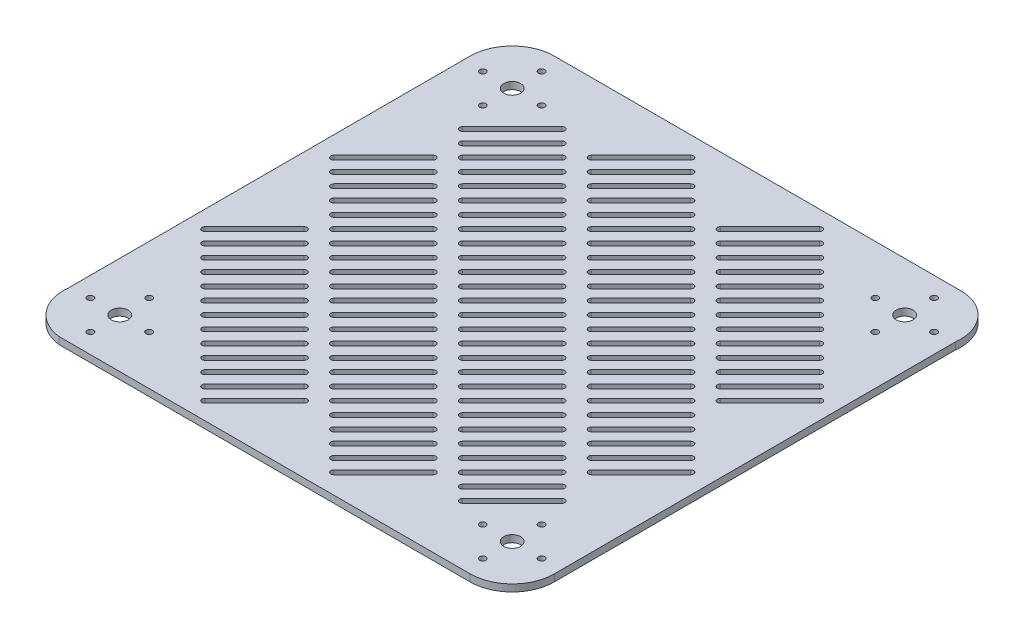
SolidWorks part; units mm, degrees
ref_plane "前视基准面" through (0, 0, 0) normal (0, 0, 1) x (1, 0, 0)
ref_plane "上视基准面" through (0, 0, 0) normal (0, 1, 0) x (1, 0, 0)
ref_plane "右视基准面" through (0, 0, 0) normal (1, 0, 0) x (0, 0, -1)
sketch "草图5" plane through (0, 0, 0) normal (0, 1, 0) x (1, 0, 0)
  line L0 (-17.6777, -17.6777) -> (17.6777, 17.6777) construction
  line L5 (-145, 175.0001) -> (144.9999, 175.0001)
  line L6 (-175.0001, 145) -> (-175.0001, -141.539)
  line L7 (-148.4608, -175.0001) -> (145, -175.0001)
  line L8 (174.7909, 141.4627) -> (175.0001, -144.9781)
  line L9 (-175.0001, 175.0001) -> (175.0001, -175.0001) construction
  line L10 (-175, -175) -> (175, 175) construction
  line L15 (-26.5165, -8.8388) -> (8.8388, 26.5165) construction
  line L18 (-28.0414, -7.3139) -> (7.3139, 28.0414)
  line L21 (-24.9916, -10.3638) -> (10.3638, 24.9916)
  line L24 (-35.3553, 0) -> (0, 35.3553) construction
  line L27 (-36.8803, 1.5249) -> (-1.5249, 36.8803)
  line L30 (-33.8304, -1.5249) -> (1.5249, 33.8304)
  line L33 (-44.1942, 8.8388) -> (-8.8388, 44.1942) construction
  line L36 (-45.7191, 10.3638) -> (-10.3638, 45.7191)
  line L39 (-42.6692, 7.3139) -> (-7.3139, 42.6692)
  line L42 (-53.033, 17.6777) -> (-17.6777, 53.033) construction
  line L45 (-54.5579, 19.2026) -> (-19.2026, 54.5579)
  line L48 (-51.5081, 16.1527) -> (-16.1527, 51.5081)
  line L51 (-61.8718, 26.5165) -> (-26.5165, 61.8718) construction
  line L54 (-63.3968, 28.0414) -> (-28.0414, 63.3968)
  line L57 (-60.3469, 24.9916) -> (-24.9916, 60.3469)
  line L60 (-70.7107, 35.3553) -> (-35.3553, 70.7107) construction
  line L63 (-72.2356, 36.8803) -> (-36.8803, 72.2356)
  line L66 (-69.1857, 33.8304) -> (-33.8304, 69.1857)
  line L69 (-79.5495, 44.1942) -> (-44.1942, 79.5495) construction
  line L72 (-81.0744, 45.7191) -> (-45.7191, 81.0744)
  line L75 (-78.0246, 42.6692) -> (-42.6692, 78.0246)
  line L78 (-88.3883, 53.033) -> (-53.033, 88.3883) construction
  line L81 (-19.2026, -16.1527) -> (16.1527, 19.2026)
  line L82 (-16.1527, -19.2026) -> (19.2026, 16.1527)
  line L83 (-89.9133, 54.5579) -> (-54.5579, 89.9133)
  line L84 (-86.8634, 51.5081) -> (-51.5081, 86.8634)
  line L85 (-97.2272, 61.8718) -> (-61.8718, 97.2272) construction
  line L86 (-98.7521, 63.3968) -> (-63.3968, 98.7521)
  line L87 (-95.7023, 60.3469) -> (-60.3469, 95.7023)
  line L88 (-106.066, 70.7107) -> (-70.7107, 106.066) construction
  line L89 (-107.5909, 72.2356) -> (-72.2356, 107.5909)
  line L90 (-104.5411, 69.1857) -> (-69.1857, 104.5411)
  line L91 (-114.9049, 79.5495) -> (-79.5495, 114.9049) construction
  line L92 (-116.4298, 81.0744) -> (-81.0744, 116.4298)
  line L93 (-113.3799, 78.0246) -> (-78.0246, 113.3799)
  line L94 (-123.7437, 88.3883) -> (-88.3883, 123.7437) construction
  line L95 (-125.2686, 89.9133) -> (-89.9133, 125.2686)
  line L96 (-122.2188, 86.8634) -> (-86.8634, 122.2188)
  line L97 (-132.5825, 97.2272) -> (-97.2272, 132.5825) construction
  line L98 (-134.1075, 98.7521) -> (-98.7521, 134.1075)
  line L99 (-131.0576, 95.7023) -> (-95.7023, 131.0576)
  line L100 (-8.8388, -26.5165) -> (26.5165, 8.8388) construction
  line L101 (-10.3638, -24.9916) -> (24.9916, 10.3638)
  line L102 (-7.3139, -28.0414) -> (28.0414, 7.3139)
  line L103 (0, -35.3553) -> (35.3553, 0) construction
  line L104 (-1.5249, -33.8304) -> (33.8304, 1.5249)
  line L105 (1.5249, -36.8803) -> (36.8803, -1.5249)
  line L106 (8.8388, -44.1942) -> (44.1942, -8.8388) construction
  line L107 (7.3139, -42.6692) -> (42.6692, -7.3139)
  line L108 (10.3638, -45.7191) -> (45.7191, -10.3638)
  line L109 (17.6777, -53.033) -> (53.033, -17.6777) construction
  line L110 (16.1527, -51.5081) -> (51.5081, -16.1527)
  line L111 (19.2026, -54.5579) -> (54.5579, -19.2026)
  line L112 (26.5165, -61.8718) -> (61.8718, -26.5165) construction
  line L113 (24.9916, -60.3469) -> (60.3469, -24.9916)
  line L114 (28.0414, -63.3968) -> (63.3968, -28.0414)
  line L115 (35.3553, -70.7107) -> (70.7107, -35.3553) construction
  line L116 (33.8304, -69.1857) -> (69.1857, -33.8304)
  line L117 (36.8803, -72.2356) -> (72.2356, -36.8803)
  line L118 (44.1942, -79.5495) -> (79.5495, -44.1942) construction
  line L119 (42.6692, -78.0246) -> (78.0246, -42.6692)
  line L120 (45.7191, -81.0744) -> (81.0744, -45.7191)
  line L121 (53.033, -88.3883) -> (88.3883, -53.033) construction
  line L122 (51.5081, -86.8634) -> (86.8634, -51.5081)
  line L123 (54.5579, -89.9133) -> (89.9133, -54.5579)
  line L124 (61.8718, -97.2272) -> (97.2272, -61.8718) construction
  line L125 (60.3469, -95.7023) -> (95.7023, -60.3469)
  line L126 (63.3968, -98.7521) -> (98.7521, -63.3968)
  line L127 (70.7107, -106.066) -> (106.066, -70.7107) construction
  line L128 (69.1857, -104.5411) -> (104.5411, -69.1857)
  line L129 (72.2356, -107.5909) -> (107.5909, -72.2356)
  line L130 (79.5495, -114.9049) -> (114.9049, -79.5495) construction
  line L131 (78.0246, -113.3799) -> (113.3799, -78.0246)
  line L132 (81.0744, -116.4298) -> (116.4298, -81.0744)
  line L133 (88.3883, -123.7437) -> (123.7437, -88.3883) construction
  line L134 (86.8634, -122.2188) -> (122.2188, -86.8634)
  line L135 (89.9133, -125.2686) -> (125.2686, -89.9133)
  line L136 (97.2272, -132.5825) -> (132.5825, -97.2272) construction
  line L137 (95.7023, -131.0576) -> (131.0576, -95.7023)
  line L138 (98.7521, -134.1075) -> (134.1075, -98.7521)
  line L139 (28.2843, 28.2843) -> (63.6396, 63.6396) construction
  line L140 (26.7593, 29.8092) -> (62.1147, 65.1645)
  line L141 (29.8092, 26.7593) -> (65.1645, 62.1147)
  line L142 (74.2462, 74.2462) -> (109.6016, 109.6016) construction
  line L143 (72.7213, 75.7711) -> (108.0766, 111.1265)
  line L144 (75.7711, 72.7213) -> (111.1265, 108.0766)
  line L145 (19.4454, 37.1231) -> (54.8008, 72.4784) construction
  line L146 (17.9205, 38.648) -> (53.2758, 74.0034)
  line L147 (20.9704, 35.5982) -> (56.3257, 70.9535)
  line L148 (10.6066, 45.9619) -> (45.9619, 81.3173) construction
  line L149 (9.0817, 47.4869) -> (44.437, 82.8422)
  line L150 (12.1315, 44.437) -> (47.4869, 79.7924)
  line L151 (1.7678, 54.8008) -> (37.1231, 90.1561) construction
  line L152 (0.2428, 56.3257) -> (35.5982, 91.681)
  line L153 (3.2927, 53.2758) -> (38.648, 88.6312)
  line L154 (-7.0711, 63.6396) -> (28.2843, 98.9949) construction
  line L155 (-8.596, 65.1645) -> (26.7593, 100.5199)
  line L156 (-5.5461, 62.1147) -> (29.8092, 97.47)
  line L157 (-15.9099, 72.4784) -> (19.4454, 107.8338) construction
  line L158 (-17.4348, 74.0034) -> (17.9205, 109.3587)
  line L159 (-14.385, 70.9535) -> (20.9704, 106.3089)
  line L160 (-24.7487, 81.3173) -> (10.6066, 116.6726) construction
  line L161 (-26.2737, 82.8422) -> (9.0817, 118.1975)
  line L162 (-23.2238, 79.7924) -> (12.1315, 115.1477)
  line L163 (-33.5876, 90.1561) -> (1.7678, 125.5115) construction
  line L164 (-35.1125, 91.681) -> (0.2428, 127.0364)
  line L165 (-32.0626, 88.6312) -> (3.2927, 123.9865)
  line L166 (-42.4264, 98.9949) -> (-7.0711, 134.3503) construction
  line L167 (-43.9513, 100.5199) -> (-8.596, 135.8752)
  line L168 (-40.9015, 97.47) -> (-5.5461, 132.8254)
  line L169 (-51.2652, 107.8338) -> (-15.9099, 143.1891) construction
  line L170 (-52.7902, 109.3587) -> (-17.4348, 144.7141)
  line L171 (-49.7403, 106.3089) -> (-14.385, 141.6642)
  line L172 (-60.1041, 116.6726) -> (-24.7487, 152.028) construction
  line L173 (-61.629, 118.1975) -> (-26.2737, 153.5529)
  line L174 (-58.5791, 115.1477) -> (-23.2238, 150.503)
  line L175 (-68.9429, 125.5115) -> (-33.5876, 160.8668) construction
  line L176 (-70.4678, 127.0364) -> (-35.1125, 162.3917)
  line L177 (-67.418, 123.9865) -> (-32.0626, 159.3419)
  line L178 (37.1231, 19.4454) -> (72.4784, 54.8008) construction
  line L179 (35.5982, 20.9704) -> (70.9535, 56.3257)
  line L180 (38.648, 17.9205) -> (74.0034, 53.2758)
  line L181 (45.9619, 10.6066) -> (81.3173, 45.9619) construction
  line L182 (44.437, 12.1315) -> (79.7924, 47.4869)
  line L183 (47.4869, 9.0817) -> (82.8422, 44.437)
  line L184 (54.8008, 1.7678) -> (90.1561, 37.1231) construction
  line L185 (53.2758, 3.2927) -> (88.6312, 38.648)
  line L186 (56.3257, 0.2428) -> (91.681, 35.5982)
  line L187 (63.6396, -7.0711) -> (98.9949, 28.2843) construction
  line L188 (62.1147, -5.5461) -> (97.47, 29.8092)
  line L189 (65.1645, -8.596) -> (100.5199, 26.7593)
  line L190 (72.4784, -15.9099) -> (107.8338, 19.4454) construction
  line L191 (70.9535, -14.385) -> (106.3089, 20.9704)
  line L192 (74.0034, -17.4348) -> (109.3587, 17.9205)
  line L193 (81.3173, -24.7487) -> (116.6726, 10.6066) construction
  line L194 (79.7924, -23.2238) -> (115.1477, 12.1315)
  line L195 (82.8422, -26.2737) -> (118.1975, 9.0817)
  line L196 (90.1561, -33.5876) -> (125.5115, 1.7678) construction
  line L197 (88.6312, -32.0626) -> (123.9865, 3.2927)
  line L198 (91.681, -35.1125) -> (127.0364, 0.2428)
  line L199 (98.9949, -42.4264) -> (134.3503, -7.0711) construction
  line L200 (97.47, -40.9015) -> (132.8254, -5.5461)
  line L201 (100.5199, -43.9513) -> (135.8752, -8.596)
  line L202 (107.8338, -51.2652) -> (143.1891, -15.9099) construction
  line L203 (106.3089, -49.7403) -> (141.6642, -14.385)
  line L204 (109.3587, -52.7902) -> (144.7141, -17.4348)
  line L205 (116.6726, -60.1041) -> (152.028, -24.7487) construction
  line L206 (115.1477, -58.5791) -> (150.503, -23.2238)
  line L207 (118.1975, -61.629) -> (153.5529, -26.2737)
  line L208 (125.5115, -68.9429) -> (160.8668, -33.5876) construction
  line L209 (123.9865, -67.418) -> (159.3419, -32.0626)
  line L210 (127.0364, -70.4678) -> (162.3917, -35.1125)
  line L211 (65.4074, 83.085) -> (100.7627, 118.4404) construction
  line L212 (63.8824, 84.61) -> (99.2378, 119.9653)
  line L213 (66.9323, 81.5601) -> (102.2876, 116.9155)
  line L214 (56.5685, 91.9239) -> (91.9239, 127.2792) construction
  line L215 (55.0436, 93.4488) -> (90.399, 128.8041)
  line L216 (58.0935, 90.399) -> (93.4488, 125.7543)
  line L217 (47.7297, 100.7627) -> (83.085, 136.1181) construction
  line L218 (46.2048, 102.2876) -> (81.5601, 137.643)
  line L219 (49.2546, 99.2378) -> (84.61, 134.5931)
  line L220 (38.8909, 109.6016) -> (74.2462, 144.9569) construction
  line L221 (37.3659, 111.1265) -> (72.7213, 146.4818)
  line L222 (40.4158, 108.0766) -> (75.7711, 143.432)
  line L223 (30.052, 118.4404) -> (65.4074, 153.7957) construction
  line L224 (28.5271, 119.9653) -> (63.8824, 155.3207)
  line L225 (31.577, 116.9155) -> (66.9323, 152.2708)
  line L226 (21.2132, 127.2792) -> (56.5685, 162.6346) construction
  line L227 (19.6883, 128.8041) -> (55.0436, 164.1595)
  line L228 (22.7381, 125.7543) -> (58.0935, 161.1096)
  line L229 (83.085, 65.4074) -> (118.4404, 100.7627) construction
  line L230 (81.5601, 66.9323) -> (116.9155, 102.2876)
  line L231 (84.61, 63.8824) -> (119.9653, 99.2378)
  line L232 (91.9239, 56.5685) -> (127.2792, 91.9239) construction
  line L233 (90.399, 58.0935) -> (125.7543, 93.4488)
  line L234 (93.4488, 55.0436) -> (128.8041, 90.399)
  line L235 (100.7627, 47.7297) -> (136.1181, 83.085) construction
  line L236 (99.2378, 49.2546) -> (134.5931, 84.61)
  line L237 (102.2876, 46.2048) -> (137.643, 81.5601)
  line L238 (109.6016, 38.8909) -> (144.9569, 74.2462) construction
  line L239 (108.0766, 40.4158) -> (143.432, 75.7711)
  line L240 (111.1265, 37.3659) -> (146.4818, 72.7213)
  line L241 (118.4404, 30.052) -> (153.7957, 65.4074) construction
  line L242 (116.9155, 31.577) -> (152.2708, 66.9323)
  line L243 (119.9653, 28.5271) -> (155.3207, 63.8824)
  line L244 (127.2792, 21.2132) -> (162.6346, 56.5685) construction
  line L245 (125.7543, 22.7381) -> (161.1096, 58.0935)
  line L246 (128.8041, 19.6883) -> (164.1595, 55.0436)
  line L247 (-63.6396, -63.6396) -> (-28.2843, -28.2843) construction
  line L248 (-65.1645, -62.1147) -> (-29.8092, -26.7593)
  line L249 (-62.1147, -65.1645) -> (-26.7593, -29.8092)
  line L250 (-109.6016, -109.6016) -> (-74.2462, -74.2462) construction
  line L251 (-111.1265, -108.0766) -> (-75.7711, -72.7213)
  line L252 (-108.0766, -111.1265) -> (-72.7213, -75.7711)
  line L253 (-72.4784, -54.8008) -> (-37.1231, -19.4454) construction
  line L254 (-74.0034, -53.2758) -> (-38.648, -17.9205)
  line L255 (-70.9535, -56.3257) -> (-35.5982, -20.9704)
  line L256 (-81.3173, -45.9619) -> (-45.9619, -10.6066) construction
  line L257 (-82.8422, -44.437) -> (-47.4869, -9.0817)
  line L258 (-79.7924, -47.4869) -> (-44.437, -12.1315)
  line L259 (-90.1561, -37.1231) -> (-54.8008, -1.7678) construction
  line L260 (-91.681, -35.5982) -> (-56.3257, -0.2428)
  line L261 (-88.6312, -38.648) -> (-53.2758, -3.2927)
  line L262 (-98.9949, -28.2843) -> (-63.6396, 7.0711) construction
  line L263 (-100.5199, -26.7593) -> (-65.1645, 8.596)
  line L264 (-97.47, -29.8092) -> (-62.1147, 5.5461)
  line L265 (-107.8338, -19.4454) -> (-72.4784, 15.9099) construction
  line L266 (-109.3587, -17.9205) -> (-74.0034, 17.4348)
  line L267 (-106.3089, -20.9704) -> (-70.9535, 14.385)
  line L268 (-116.6726, -10.6066) -> (-81.3173, 24.7487) construction
  line L269 (-118.1975, -9.0817) -> (-82.8422, 26.2737)
  line L270 (-115.1477, -12.1315) -> (-79.7924, 23.2238)
  line L271 (-125.5115, -1.7678) -> (-90.1561, 33.5876) construction
  line L272 (-127.0364, -0.2428) -> (-91.681, 35.1125)
  line L273 (-123.9865, -3.2927) -> (-88.6312, 32.0626)
  line L274 (-134.3503, 7.0711) -> (-98.9949, 42.4264) construction
  line L275 (-135.8752, 8.596) -> (-100.5199, 43.9513)
  line L276 (-132.8254, 5.5461) -> (-97.47, 40.9015)
  line L277 (-143.1891, 15.9099) -> (-107.8338, 51.2652) construction
  line L278 (-144.7141, 17.4348) -> (-109.3587, 52.7902)
  line L279 (-141.6642, 14.385) -> (-106.3089, 49.7403)
  line L280 (-152.028, 24.7487) -> (-116.6726, 60.1041) construction
  line L281 (-153.5529, 26.2737) -> (-118.1975, 61.629)
  line L282 (-150.503, 23.2238) -> (-115.1477, 58.5791)
  line L283 (-160.8668, 33.5876) -> (-125.5115, 68.9429) construction
  line L284 (-162.3917, 35.1125) -> (-127.0364, 70.4678)
  line L285 (-159.3419, 32.0626) -> (-123.9865, 67.418)
  line L286 (-54.8008, -72.4784) -> (-19.4454, -37.1231) construction
  line L287 (-56.3257, -70.9535) -> (-20.9704, -35.5982)
  line L288 (-53.2758, -74.0034) -> (-17.9205, -38.648)
  line L289 (-45.9619, -81.3173) -> (-10.6066, -45.9619) construction
  line L290 (-47.4869, -79.7924) -> (-12.1315, -44.437)
  line L291 (-44.437, -82.8422) -> (-9.0817, -47.4869)
  line L292 (-37.1231, -90.1561) -> (-1.7678, -54.8008) construction
  line L293 (-38.648, -88.6312) -> (-3.2927, -53.2758)
  line L294 (-35.5982, -91.681) -> (-0.2428, -56.3257)
  line L295 (-28.2843, -98.9949) -> (7.0711, -63.6396) construction
  line L296 (-29.8092, -97.47) -> (5.5461, -62.1147)
  line L297 (-26.7593, -100.5199) -> (8.596, -65.1645)
  line L298 (-19.4454, -107.8338) -> (15.9099, -72.4784) construction
  line L299 (-20.9704, -106.3089) -> (14.385, -70.9535)
  line L300 (-17.9205, -109.3587) -> (17.4348, -74.0034)
  line L301 (-10.6066, -116.6726) -> (24.7487, -81.3173) construction
  line L302 (-12.1315, -115.1477) -> (23.2238, -79.7924)
  line L303 (-9.0817, -118.1975) -> (26.2737, -82.8422)
  line L304 (-1.7678, -125.5115) -> (33.5876, -90.1561) construction
  line L305 (-3.2927, -123.9865) -> (32.0626, -88.6312)
  line L306 (-0.2428, -127.0364) -> (35.1125, -91.681)
  line L307 (7.0711, -134.3503) -> (42.4264, -98.9949) construction
  line L308 (5.5461, -132.8254) -> (40.9015, -97.47)
  line L309 (8.596, -135.8752) -> (43.9513, -100.5199)
  line L310 (15.9099, -143.1891) -> (51.2652, -107.8338) construction
  line L311 (14.385, -141.6642) -> (49.7403, -106.3089)
  line L312 (17.4348, -144.7141) -> (52.7902, -109.3587)
  line L313 (24.7487, -152.028) -> (60.1041, -116.6726) construction
  line L314 (23.2238, -150.503) -> (58.5791, -115.1477)
  line L315 (26.2737, -153.5529) -> (61.629, -118.1975)
  line L316 (33.5876, -160.8668) -> (68.9429, -125.5115) construction
  line L317 (32.0626, -159.3419) -> (67.418, -123.9865)
  line L318 (35.1125, -162.3917) -> (70.4678, -127.0364)
  line L319 (-100.7627, -118.4404) -> (-65.4074, -83.085) construction
  line L320 (-102.2876, -116.9155) -> (-66.9323, -81.5601)
  line L321 (-99.2378, -119.9653) -> (-63.8824, -84.61)
  line L322 (-91.9239, -127.2792) -> (-56.5685, -91.9239) construction
  line L323 (-93.4488, -125.7543) -> (-58.0935, -90.399)
  line L324 (-90.399, -128.8041) -> (-55.0436, -93.4488)
  line L325 (-83.085, -136.1181) -> (-47.7297, -100.7627) construction
  line L326 (-84.61, -134.5931) -> (-49.2546, -99.2378)
  line L327 (-81.5601, -137.643) -> (-46.2048, -102.2876)
  line L328 (-74.2462, -144.9569) -> (-38.8909, -109.6016) construction
  line L329 (-75.7711, -143.432) -> (-40.4158, -108.0766)
  line L330 (-72.7213, -146.4818) -> (-37.3659, -111.1265)
  line L331 (-65.4074, -153.7957) -> (-30.052, -118.4404) construction
  line L332 (-66.9323, -152.2708) -> (-31.577, -116.9155)
  line L333 (-63.8824, -155.3207) -> (-28.5271, -119.9653)
  line L334 (-56.5685, -162.6346) -> (-21.2132, -127.2792) construction
  line L335 (-58.0935, -161.1096) -> (-22.7381, -125.7543)
  line L336 (-55.0436, -164.1595) -> (-19.6883, -128.8041)
  line L337 (-118.4404, -100.7627) -> (-83.085, -65.4074) construction
  line L338 (-119.9653, -99.2378) -> (-84.61, -63.8824)
  line L339 (-116.9155, -102.2876) -> (-81.5601, -66.9323)
  line L340 (-127.2792, -91.9239) -> (-91.9239, -56.5685) construction
  line L341 (-128.8041, -90.399) -> (-93.4488, -55.0436)
  line L342 (-125.7543, -93.4488) -> (-90.399, -58.0935)
  line L343 (-136.1181, -83.085) -> (-100.7627, -47.7297) construction
  line L344 (-137.643, -81.5601) -> (-102.2876, -46.2048)
  line L345 (-134.5931, -84.61) -> (-99.2378, -49.2546)
  line L346 (-144.9569, -74.2462) -> (-109.6016, -38.8909) construction
  line L347 (-146.4818, -72.7213) -> (-111.1265, -37.3659)
  line L348 (-143.432, -75.7711) -> (-108.0766, -40.4158)
  line L349 (-153.7957, -65.4074) -> (-118.4404, -30.052) construction
  line L350 (-155.3207, -63.8824) -> (-119.9653, -28.5271)
  line L351 (-152.2708, -66.9323) -> (-116.9155, -31.577)
  line L352 (-162.6346, -56.5685) -> (-127.2792, -21.2132) construction
  line L353 (-164.1595, -55.0436) -> (-128.8041, -19.6883)
  line L354 (-161.1096, -58.0935) -> (-125.7543, -22.7381)
  arc A0 (174.7909, 141.4627) -> (144.9999, 175.0001) centre (144.9999, 144.9999) ccw
  arc A1 (175.0001, -144.9781) -> (145, -175.0001) centre (145, -145) cw
  arc A2 (-148.4608, -175.0001) -> (-175.0001, -141.539) centre (-144.9999, -144.9999) cw
  arc A3 (-175.0001, 145) -> (-145, 175.0001) centre (-145, 145) cw
  circle A5 centre (140, 119) radius 2.25
  circle A6 centre (161, 140) radius 2.25
  circle A7 centre (140, 161) radius 2.25
  circle A8 centre (119, 140) radius 2.25
  circle A9 centre (140, 140) radius 6.02
  circle A11 centre (140, -161) radius 2.25
  circle A12 centre (161, -140) radius 2.25
  circle A13 centre (140, -119) radius 2.25
  circle A14 centre (119, -140) radius 2.25
  circle A15 centre (140, -140) radius 6.02
  circle A17 centre (-140, 119) radius 2.25
  circle A18 centre (-119, 140) radius 2.25
  circle A19 centre (-140, 161) radius 2.25
  circle A20 centre (-161, 140) radius 2.25
  circle A21 centre (-140, 140) radius 6.02
  circle A23 centre (-140, -161) radius 2.25
  circle A24 centre (-119, -140.0405) radius 2.25
  circle A25 centre (-140, -119) radius 2.25
  circle A26 centre (-161, -140) radius 2.25
  circle A27 centre (-140, -140.0405) radius 6.02
  arc A76 (-19.2026, -16.1527) -> (-16.1527, -19.2026) centre (-17.6777, -17.6777) ccw
  arc A77 (19.2026, 16.1527) -> (16.1527, 19.2026) centre (17.6777, 17.6777) ccw
  arc A78 (-28.0414, -7.3139) -> (-24.9916, -10.3638) centre (-26.5165, -8.8388) ccw
  arc A79 (10.3638, 24.9916) -> (7.3139, 28.0414) centre (8.8388, 26.5165) ccw
  arc A80 (-36.8803, 1.5249) -> (-33.8304, -1.5249) centre (-35.3553, 0) ccw
  arc A81 (1.5249, 33.8304) -> (-1.5249, 36.8803) centre (0, 35.3553) ccw
  arc A82 (-45.7191, 10.3638) -> (-42.6692, 7.3139) centre (-44.1942, 8.8388) ccw
  arc A83 (-7.3139, 42.6692) -> (-10.3638, 45.7191) centre (-8.8388, 44.1942) ccw
  arc A84 (-54.5579, 19.2026) -> (-51.5081, 16.1527) centre (-53.033, 17.6777) ccw
  arc A85 (-16.1527, 51.5081) -> (-19.2026, 54.5579) centre (-17.6777, 53.033) ccw
  arc A86 (-63.3968, 28.0414) -> (-60.3469, 24.9916) centre (-61.8718, 26.5165) ccw
  arc A87 (-24.9916, 60.3469) -> (-28.0414, 63.3968) centre (-26.5165, 61.8718) ccw
  arc A88 (-72.2356, 36.8803) -> (-69.1857, 33.8304) centre (-70.7107, 35.3553) ccw
  arc A89 (-33.8304, 69.1857) -> (-36.8803, 72.2356) centre (-35.3553, 70.7107) ccw
  arc A90 (-81.0744, 45.7191) -> (-78.0246, 42.6692) centre (-79.5495, 44.1942) ccw
  arc A91 (-42.6692, 78.0246) -> (-45.7191, 81.0744) centre (-44.1942, 79.5495) ccw
  arc A92 (-89.9133, 54.5579) -> (-86.8634, 51.5081) centre (-88.3883, 53.033) ccw
  arc A93 (-51.5081, 86.8634) -> (-54.5579, 89.9133) centre (-53.033, 88.3883) ccw
  arc A94 (-98.7521, 63.3968) -> (-95.7023, 60.3469) centre (-97.2272, 61.8718) ccw
  arc A95 (-60.3469, 95.7023) -> (-63.3968, 98.7521) centre (-61.8718, 97.2272) ccw
  arc A96 (-107.5909, 72.2356) -> (-104.5411, 69.1857) centre (-106.066, 70.7107) ccw
  arc A97 (-69.1857, 104.5411) -> (-72.2356, 107.5909) centre (-70.7107, 106.066) ccw
  arc A98 (-116.4298, 81.0744) -> (-113.3799, 78.0246) centre (-114.9049, 79.5495) ccw
  arc A99 (-78.0246, 113.3799) -> (-81.0744, 116.4298) centre (-79.5495, 114.9049) ccw
  arc A100 (-125.2686, 89.9133) -> (-122.2188, 86.8634) centre (-123.7437, 88.3883) ccw
  arc A101 (-86.8634, 122.2188) -> (-89.9133, 125.2686) centre (-88.3883, 123.7437) ccw
  arc A102 (-134.1075, 98.7521) -> (-131.0576, 95.7023) centre (-132.5825, 97.2272) ccw
  arc A103 (-95.7023, 131.0576) -> (-98.7521, 134.1075) centre (-97.2272, 132.5825) ccw
  arc A104 (-10.3638, -24.9916) -> (-7.3139, -28.0414) centre (-8.8388, -26.5165) ccw
  arc A105 (28.0414, 7.3139) -> (24.9916, 10.3638) centre (26.5165, 8.8388) ccw
  arc A106 (-1.5249, -33.8304) -> (1.5249, -36.8803) centre (0, -35.3553) ccw
  arc A107 (36.8803, -1.5249) -> (33.8304, 1.5249) centre (35.3553, 0) ccw
  arc A108 (7.3139, -42.6692) -> (10.3638, -45.7191) centre (8.8388, -44.1942) ccw
  arc A109 (45.7191, -10.3638) -> (42.6692, -7.3139) centre (44.1942, -8.8388) ccw
  arc A110 (16.1527, -51.5081) -> (19.2026, -54.5579) centre (17.6777, -53.033) ccw
  arc A111 (54.5579, -19.2026) -> (51.5081, -16.1527) centre (53.033, -17.6777) ccw
  arc A112 (24.9916, -60.3469) -> (28.0414, -63.3968) centre (26.5165, -61.8718) ccw
  arc A113 (63.3968, -28.0414) -> (60.3469, -24.9916) centre (61.8718, -26.5165) ccw
  arc A114 (33.8304, -69.1857) -> (36.8803, -72.2356) centre (35.3553, -70.7107) ccw
  arc A115 (72.2356, -36.8803) -> (69.1857, -33.8304) centre (70.7107, -35.3553) ccw
  arc A116 (42.6692, -78.0246) -> (45.7191, -81.0744) centre (44.1942, -79.5495) ccw
  arc A117 (81.0744, -45.7191) -> (78.0246, -42.6692) centre (79.5495, -44.1942) ccw
  arc A118 (51.5081, -86.8634) -> (54.5579, -89.9133) centre (53.033, -88.3883) ccw
  arc A119 (89.9133, -54.5579) -> (86.8634, -51.5081) centre (88.3883, -53.033) ccw
  arc A120 (60.3469, -95.7023) -> (63.3968, -98.7521) centre (61.8718, -97.2272) ccw
  arc A121 (98.7521, -63.3968) -> (95.7023, -60.3469) centre (97.2272, -61.8718) ccw
  arc A122 (69.1857, -104.5411) -> (72.2356, -107.5909) centre (70.7107, -106.066) ccw
  arc A123 (107.5909, -72.2356) -> (104.5411, -69.1857) centre (106.066, -70.7107) ccw
  arc A124 (78.0246, -113.3799) -> (81.0744, -116.4298) centre (79.5495, -114.9049) ccw
  arc A125 (116.4298, -81.0744) -> (113.3799, -78.0246) centre (114.9049, -79.5495) ccw
  arc A126 (86.8634, -122.2188) -> (89.9133, -125.2686) centre (88.3883, -123.7437) ccw
  arc A127 (125.2686, -89.9133) -> (122.2188, -86.8634) centre (123.7437, -88.3883) ccw
  arc A128 (95.7023, -131.0576) -> (98.7521, -134.1075) centre (97.2272, -132.5825) ccw
  arc A129 (134.1075, -98.7521) -> (131.0576, -95.7023) centre (132.5825, -97.2272) ccw
  arc A130 (26.7593, 29.8092) -> (29.8092, 26.7593) centre (28.2843, 28.2843) ccw
  arc A131 (65.1645, 62.1147) -> (62.1147, 65.1645) centre (63.6396, 63.6396) ccw
  arc A132 (72.7213, 75.7711) -> (75.7711, 72.7213) centre (74.2462, 74.2462) ccw
  arc A133 (111.1265, 108.0766) -> (108.0766, 111.1265) centre (109.6016, 109.6016) ccw
  arc A134 (17.9205, 38.648) -> (20.9704, 35.5982) centre (19.4454, 37.1231) ccw
  arc A135 (56.3257, 70.9535) -> (53.2758, 74.0034) centre (54.8008, 72.4784) ccw
  arc A136 (9.0817, 47.4869) -> (12.1315, 44.437) centre (10.6066, 45.9619) ccw
  arc A137 (47.4869, 79.7924) -> (44.437, 82.8422) centre (45.9619, 81.3173) ccw
  arc A138 (0.2428, 56.3257) -> (3.2927, 53.2758) centre (1.7678, 54.8008) ccw
  arc A139 (38.648, 88.6312) -> (35.5982, 91.681) centre (37.1231, 90.1561) ccw
  arc A140 (-8.596, 65.1645) -> (-5.5461, 62.1147) centre (-7.0711, 63.6396) ccw
  arc A141 (29.8092, 97.47) -> (26.7593, 100.5199) centre (28.2843, 98.9949) ccw
  arc A142 (-17.4348, 74.0034) -> (-14.385, 70.9535) centre (-15.9099, 72.4784) ccw
  arc A143 (20.9704, 106.3089) -> (17.9205, 109.3587) centre (19.4454, 107.8338) ccw
  arc A144 (-26.2737, 82.8422) -> (-23.2238, 79.7924) centre (-24.7487, 81.3173) ccw
  arc A145 (12.1315, 115.1477) -> (9.0817, 118.1975) centre (10.6066, 116.6726) ccw
  arc A146 (-35.1125, 91.681) -> (-32.0626, 88.6312) centre (-33.5876, 90.1561) ccw
  arc A147 (3.2927, 123.9865) -> (0.2428, 127.0364) centre (1.7678, 125.5115) ccw
  arc A148 (-43.9513, 100.5199) -> (-40.9015, 97.47) centre (-42.4264, 98.9949) ccw
  arc A149 (-5.5461, 132.8254) -> (-8.596, 135.8752) centre (-7.0711, 134.3503) ccw
  arc A150 (-52.7902, 109.3587) -> (-49.7403, 106.3089) centre (-51.2652, 107.8338) ccw
  arc A151 (-14.385, 141.6642) -> (-17.4348, 144.7141) centre (-15.9099, 143.1891) ccw
  arc A152 (-61.629, 118.1975) -> (-58.5791, 115.1477) centre (-60.1041, 116.6726) ccw
  arc A153 (-23.2238, 150.503) -> (-26.2737, 153.5529) centre (-24.7487, 152.028) ccw
  arc A154 (-70.4678, 127.0364) -> (-67.418, 123.9865) centre (-68.9429, 125.5115) ccw
  arc A155 (-32.0626, 159.3419) -> (-35.1125, 162.3917) centre (-33.5876, 160.8668) ccw
  arc A156 (35.5982, 20.9704) -> (38.648, 17.9205) centre (37.1231, 19.4454) ccw
  arc A157 (74.0034, 53.2758) -> (70.9535, 56.3257) centre (72.4784, 54.8008) ccw
  arc A158 (44.437, 12.1315) -> (47.4869, 9.0817) centre (45.9619, 10.6066) ccw
  arc A159 (82.8422, 44.437) -> (79.7924, 47.4869) centre (81.3173, 45.9619) ccw
  arc A160 (53.2758, 3.2927) -> (56.3257, 0.2428) centre (54.8008, 1.7678) ccw
  arc A161 (91.681, 35.5982) -> (88.6312, 38.648) centre (90.1561, 37.1231) ccw
  arc A162 (62.1147, -5.5461) -> (65.1645, -8.596) centre (63.6396, -7.0711) ccw
  arc A163 (100.5199, 26.7593) -> (97.47, 29.8092) centre (98.9949, 28.2843) ccw
  arc A164 (70.9535, -14.385) -> (74.0034, -17.4348) centre (72.4784, -15.9099) ccw
  arc A165 (109.3587, 17.9205) -> (106.3089, 20.9704) centre (107.8338, 19.4454) ccw
  arc A166 (79.7924, -23.2238) -> (82.8422, -26.2737) centre (81.3173, -24.7487) ccw
  arc A167 (118.1975, 9.0817) -> (115.1477, 12.1315) centre (116.6726, 10.6066) ccw
  arc A168 (88.6312, -32.0626) -> (91.681, -35.1125) centre (90.1561, -33.5876) ccw
  arc A169 (127.0364, 0.2428) -> (123.9865, 3.2927) centre (125.5115, 1.7678) ccw
  arc A170 (97.47, -40.9015) -> (100.5199, -43.9513) centre (98.9949, -42.4264) ccw
  arc A171 (135.8752, -8.596) -> (132.8254, -5.5461) centre (134.3503, -7.0711) ccw
  arc A172 (106.3089, -49.7403) -> (109.3587, -52.7902) centre (107.8338, -51.2652) ccw
  arc A173 (144.7141, -17.4348) -> (141.6642, -14.385) centre (143.1891, -15.9099) ccw
  arc A174 (115.1477, -58.5791) -> (118.1975, -61.629) centre (116.6726, -60.1041) ccw
  arc A175 (153.5529, -26.2737) -> (150.503, -23.2238) centre (152.028, -24.7487) ccw
  arc A176 (123.9865, -67.418) -> (127.0364, -70.4678) centre (125.5115, -68.9429) ccw
  arc A177 (162.3917, -35.1125) -> (159.3419, -32.0626) centre (160.8668, -33.5876) ccw
  arc A178 (63.8824, 84.61) -> (66.9323, 81.5601) centre (65.4074, 83.085) ccw
  arc A179 (102.2876, 116.9155) -> (99.2378, 119.9653) centre (100.7627, 118.4404) ccw
  arc A180 (55.0436, 93.4488) -> (58.0935, 90.399) centre (56.5685, 91.9239) ccw
  arc A181 (93.4488, 125.7543) -> (90.399, 128.8041) centre (91.9239, 127.2792) ccw
  arc A182 (46.2048, 102.2876) -> (49.2546, 99.2378) centre (47.7297, 100.7627) ccw
  arc A183 (84.61, 134.5931) -> (81.5601, 137.643) centre (83.085, 136.1181) ccw
  arc A184 (37.3659, 111.1265) -> (40.4158, 108.0766) centre (38.8909, 109.6016) ccw
  arc A185 (75.7711, 143.432) -> (72.7213, 146.4818) centre (74.2462, 144.9569) ccw
  arc A186 (28.5271, 119.9653) -> (31.577, 116.9155) centre (30.052, 118.4404) ccw
  arc A187 (66.9323, 152.2708) -> (63.8824, 155.3207) centre (65.4074, 153.7957) ccw
  arc A188 (19.6883, 128.8041) -> (22.7381, 125.7543) centre (21.2132, 127.2792) ccw
  arc A189 (58.0935, 161.1096) -> (55.0436, 164.1595) centre (56.5685, 162.6346) ccw
  arc A190 (81.5601, 66.9323) -> (84.61, 63.8824) centre (83.085, 65.4074) ccw
  arc A191 (119.9653, 99.2378) -> (116.9155, 102.2876) centre (118.4404, 100.7627) ccw
  arc A192 (90.399, 58.0935) -> (93.4488, 55.0436) centre (91.9239, 56.5685) ccw
  arc A193 (128.8041, 90.399) -> (125.7543, 93.4488) centre (127.2792, 91.9239) ccw
  arc A194 (99.2378, 49.2546) -> (102.2876, 46.2048) centre (100.7627, 47.7297) ccw
  arc A195 (137.643, 81.5601) -> (134.5931, 84.61) centre (136.1181, 83.085) ccw
  arc A196 (108.0766, 40.4158) -> (111.1265, 37.3659) centre (109.6016, 38.8909) ccw
  arc A197 (146.4818, 72.7213) -> (143.432, 75.7711) centre (144.9569, 74.2462) ccw
  arc A198 (116.9155, 31.577) -> (119.9653, 28.5271) centre (118.4404, 30.052) ccw
  arc A199 (155.3207, 63.8824) -> (152.2708, 66.9323) centre (153.7957, 65.4074) ccw
  arc A200 (125.7543, 22.7381) -> (128.8041, 19.6883) centre (127.2792, 21.2132) ccw
  arc A201 (164.1595, 55.0436) -> (161.1096, 58.0935) centre (162.6346, 56.5685) ccw
  arc A202 (-65.1645, -62.1147) -> (-62.1147, -65.1645) centre (-63.6396, -63.6396) ccw
  arc A203 (-26.7593, -29.8092) -> (-29.8092, -26.7593) centre (-28.2843, -28.2843) ccw
  arc A204 (-111.1265, -108.0766) -> (-108.0766, -111.1265) centre (-109.6016, -109.6016) ccw
  arc A205 (-72.7213, -75.7711) -> (-75.7711, -72.7213) centre (-74.2462, -74.2462) ccw
  arc A206 (-74.0034, -53.2758) -> (-70.9535, -56.3257) centre (-72.4784, -54.8008) ccw
  arc A207 (-35.5982, -20.9704) -> (-38.648, -17.9205) centre (-37.1231, -19.4454) ccw
  arc A208 (-82.8422, -44.437) -> (-79.7924, -47.4869) centre (-81.3173, -45.9619) ccw
  arc A209 (-44.437, -12.1315) -> (-47.4869, -9.0817) centre (-45.9619, -10.6066) ccw
  arc A210 (-91.681, -35.5982) -> (-88.6312, -38.648) centre (-90.1561, -37.1231) ccw
  arc A211 (-53.2758, -3.2927) -> (-56.3257, -0.2428) centre (-54.8008, -1.7678) ccw
  arc A212 (-100.5199, -26.7593) -> (-97.47, -29.8092) centre (-98.9949, -28.2843) ccw
  arc A213 (-62.1147, 5.5461) -> (-65.1645, 8.596) centre (-63.6396, 7.0711) ccw
  arc A214 (-109.3587, -17.9205) -> (-106.3089, -20.9704) centre (-107.8338, -19.4454) ccw
  arc A215 (-70.9535, 14.385) -> (-74.0034, 17.4348) centre (-72.4784, 15.9099) ccw
  arc A216 (-118.1975, -9.0817) -> (-115.1477, -12.1315) centre (-116.6726, -10.6066) ccw
  arc A217 (-79.7924, 23.2238) -> (-82.8422, 26.2737) centre (-81.3173, 24.7487) ccw
  arc A218 (-127.0364, -0.2428) -> (-123.9865, -3.2927) centre (-125.5115, -1.7678) ccw
  arc A219 (-88.6312, 32.0626) -> (-91.681, 35.1125) centre (-90.1561, 33.5876) ccw
  arc A220 (-135.8752, 8.596) -> (-132.8254, 5.5461) centre (-134.3503, 7.0711) ccw
  arc A221 (-97.47, 40.9015) -> (-100.5199, 43.9513) centre (-98.9949, 42.4264) ccw
  arc A222 (-144.7141, 17.4348) -> (-141.6642, 14.385) centre (-143.1891, 15.9099) ccw
  arc A223 (-106.3089, 49.7403) -> (-109.3587, 52.7902) centre (-107.8338, 51.2652) ccw
  arc A224 (-153.5529, 26.2737) -> (-150.503, 23.2238) centre (-152.028, 24.7487) ccw
  arc A225 (-115.1477, 58.5791) -> (-118.1975, 61.629) centre (-116.6726, 60.1041) ccw
  arc A226 (-162.3917, 35.1125) -> (-159.3419, 32.0626) centre (-160.8668, 33.5876) ccw
  arc A227 (-123.9865, 67.418) -> (-127.0364, 70.4678) centre (-125.5115, 68.9429) ccw
  arc A228 (-56.3257, -70.9535) -> (-53.2758, -74.0034) centre (-54.8008, -72.4784) ccw
  arc A229 (-17.9205, -38.648) -> (-20.9704, -35.5982) centre (-19.4454, -37.1231) ccw
  arc A230 (-47.4869, -79.7924) -> (-44.437, -82.8422) centre (-45.9619, -81.3173) ccw
  arc A231 (-9.0817, -47.4869) -> (-12.1315, -44.437) centre (-10.6066, -45.9619) ccw
  arc A232 (-38.648, -88.6312) -> (-35.5982, -91.681) centre (-37.1231, -90.1561) ccw
  arc A233 (-0.2428, -56.3257) -> (-3.2927, -53.2758) centre (-1.7678, -54.8008) ccw
  arc A234 (-29.8092, -97.47) -> (-26.7593, -100.5199) centre (-28.2843, -98.9949) ccw
  arc A235 (8.596, -65.1645) -> (5.5461, -62.1147) centre (7.0711, -63.6396) ccw
  arc A236 (-20.9704, -106.3089) -> (-17.9205, -109.3587) centre (-19.4454, -107.8338) ccw
  arc A237 (17.4348, -74.0034) -> (14.385, -70.9535) centre (15.9099, -72.4784) ccw
  arc A238 (-12.1315, -115.1477) -> (-9.0817, -118.1975) centre (-10.6066, -116.6726) ccw
  arc A239 (26.2737, -82.8422) -> (23.2238, -79.7924) centre (24.7487, -81.3173) ccw
  arc A240 (-3.2927, -123.9865) -> (-0.2428, -127.0364) centre (-1.7678, -125.5115) ccw
  arc A241 (35.1125, -91.681) -> (32.0626, -88.6312) centre (33.5876, -90.1561) ccw
  arc A242 (5.5461, -132.8254) -> (8.596, -135.8752) centre (7.0711, -134.3503) ccw
  arc A243 (43.9513, -100.5199) -> (40.9015, -97.47) centre (42.4264, -98.9949) ccw
  arc A244 (14.385, -141.6642) -> (17.4348, -144.7141) centre (15.9099, -143.1891) ccw
  arc A245 (52.7902, -109.3587) -> (49.7403, -106.3089) centre (51.2652, -107.8338) ccw
  arc A246 (23.2238, -150.503) -> (26.2737, -153.5529) centre (24.7487, -152.028) ccw
  arc A247 (61.629, -118.1975) -> (58.5791, -115.1477) centre (60.1041, -116.6726) ccw
  arc A248 (32.0626, -159.3419) -> (35.1125, -162.3917) centre (33.5876, -160.8668) ccw
  arc A249 (70.4678, -127.0364) -> (67.418, -123.9865) centre (68.9429, -125.5115) ccw
  arc A250 (-102.2876, -116.9155) -> (-99.2378, -119.9653) centre (-100.7627, -118.4404) ccw
  arc A251 (-63.8824, -84.61) -> (-66.9323, -81.5601) centre (-65.4074, -83.085) ccw
  arc A252 (-93.4488, -125.7543) -> (-90.399, -128.8041) centre (-91.9239, -127.2792) ccw
  arc A253 (-55.0436, -93.4488) -> (-58.0935, -90.399) centre (-56.5685, -91.9239) ccw
  arc A254 (-84.61, -134.5931) -> (-81.5601, -137.643) centre (-83.085, -136.1181) ccw
  arc A255 (-46.2048, -102.2876) -> (-49.2546, -99.2378) centre (-47.7297, -100.7627) ccw
  arc A256 (-75.7711, -143.432) -> (-72.7213, -146.4818) centre (-74.2462, -144.9569) ccw
  arc A257 (-37.3659, -111.1265) -> (-40.4158, -108.0766) centre (-38.8909, -109.6016) ccw
  arc A258 (-66.9323, -152.2708) -> (-63.8824, -155.3207) centre (-65.4074, -153.7957) ccw
  arc A259 (-28.5271, -119.9653) -> (-31.577, -116.9155) centre (-30.052, -118.4404) ccw
  arc A260 (-58.0935, -161.1096) -> (-55.0436, -164.1595) centre (-56.5685, -162.6346) ccw
  arc A261 (-19.6883, -128.8041) -> (-22.7381, -125.7543) centre (-21.2132, -127.2792) ccw
  arc A262 (-119.9653, -99.2378) -> (-116.9155, -102.2876) centre (-118.4404, -100.7627) ccw
  arc A263 (-81.5601, -66.9323) -> (-84.61, -63.8824) centre (-83.085, -65.4074) ccw
  arc A264 (-128.8041, -90.399) -> (-125.7543, -93.4488) centre (-127.2792, -91.9239) ccw
  arc A265 (-90.399, -58.0935) -> (-93.4488, -55.0436) centre (-91.9239, -56.5685) ccw
  arc A266 (-137.643, -81.5601) -> (-134.5931, -84.61) centre (-136.1181, -83.085) ccw
  arc A267 (-99.2378, -49.2546) -> (-102.2876, -46.2048) centre (-100.7627, -47.7297) ccw
  arc A268 (-146.4818, -72.7213) -> (-143.432, -75.7711) centre (-144.9569, -74.2462) ccw
  arc A269 (-108.0766, -40.4158) -> (-111.1265, -37.3659) centre (-109.6016, -38.8909) ccw
  arc A270 (-155.3207, -63.8824) -> (-152.2708, -66.9323) centre (-153.7957, -65.4074) ccw
  arc A271 (-116.9155, -31.577) -> (-119.9653, -28.5271) centre (-118.4404, -30.052) ccw
  arc A272 (-164.1595, -55.0436) -> (-161.1096, -58.0935) centre (-162.6346, -56.5685) ccw
  arc A273 (-125.7543, -22.7381) -> (-128.8041, -19.6883) centre (-127.2792, -21.2132) ccw
  point P0 (0, 0)
  point P5 (144.9999, 144.9999)
  point P19 (140, 140)
  point P31 (140, -140)
  point P32 (-140, 140)
  point P35 (0, 0)
  point P57 (-140, -140)
  point P65 (-8.8388, 8.8388)
  point P81 (-17.6777, 17.6777)
  point P88 (-26.5165, 26.5165)
  point P95 (-35.3553, 35.3553)
  point P102 (-44.1942, 44.1942)
  point P109 (-53.033, 53.033)
  point P116 (-61.8718, 61.8718)
  point P123 (-70.7107, 70.7107)
  point P130 (-79.5495, 79.5495)
  point P137 (-88.3883, 88.3883)
  point P144 (-97.2272, 97.2272)
  point P151 (-106.066, 106.066)
  point P158 (-114.9049, 114.9049)
  point P164 (8.8388, -8.8388)
  point P171 (17.6777, -17.6777)
  point P178 (26.5165, -26.5165)
  point P185 (35.3553, -35.3553)
  point P192 (44.1942, -44.1942)
  point P199 (53.033, -53.033)
  point P206 (61.8718, -61.8718)
  point P213 (70.7107, -70.7107)
  point P220 (79.5495, -79.5495)
  point P227 (88.3883, -88.3883)
  point P234 (97.2272, -97.2272)
  point P241 (106.066, -106.066)
  point P248 (114.9049, -114.9049)
  point P256 (45.9619, 45.9619)
  point P263 (91.9239, 91.9239)
  point P269 (37.1231, 54.8008)
  point P276 (28.2843, 63.6396)
  point P283 (19.4454, 72.4784)
  point P290 (10.6066, 81.3173)
  point P297 (1.7678, 90.1561)
  point P304 (-7.0711, 98.9949)
  point P311 (-15.9099, 107.8338)
  point P318 (-24.7487, 116.6726)
  point P325 (-33.5876, 125.5115)
  point P332 (-42.4264, 134.3503)
  point P339 (-51.2652, 143.1891)
  point P347 (54.8008, 37.1231)
  point P354 (63.6396, 28.2843)
  point P361 (72.4784, 19.4454)
  point P368 (81.3173, 10.6066)
  point P375 (90.1561, 1.7678)
  point P382 (98.9949, -7.0711)
  point P389 (107.8338, -15.9099)
  point P396 (116.6726, -24.7487)
  point P403 (125.5115, -33.5876)
  point P410 (134.3503, -42.4264)
  point P417 (143.1891, -51.2652)
  point P423 (83.085, 100.7627)
  point P430 (74.2462, 109.6016)
  point P437 (65.4074, 118.4404)
  point P444 (56.5685, 127.2792)
  point P451 (47.7297, 136.1181)
  point P458 (38.8909, 144.9569)
  point P465 (100.7627, 83.085)
  point P472 (109.6016, 74.2462)
  point P479 (118.4404, 65.4074)
  point P486 (127.2792, 56.5685)
  point P493 (136.1181, 47.7297)
  point P500 (144.9569, 38.8909)
  point P507 (-45.9619, -45.9619)
  point P514 (-91.9239, -91.9239)
  point P522 (-54.8008, -37.1231)
  point P529 (-63.6396, -28.2843)
  point P536 (-72.4784, -19.4454)
  point P543 (-81.3173, -10.6066)
  point P550 (-90.1561, -1.7678)
  point P557 (-98.9949, 7.0711)
  point P564 (-107.8338, 15.9099)
  point P571 (-116.6726, 24.7487)
  point P578 (-125.5115, 33.5876)
  point P585 (-134.3503, 42.4264)
  point P592 (-143.1891, 51.2652)
  point P598 (-37.1231, -54.8008)
  point P605 (-28.2843, -63.6396)
  point P612 (-19.4454, -72.4784)
  point P619 (-10.6066, -81.3173)
  point P626 (-1.7678, -90.1561)
  point P633 (7.0711, -98.9949)
  point P640 (15.9099, -107.8338)
  point P647 (24.7487, -116.6726)
  point P654 (33.5876, -125.5115)
  point P661 (42.4264, -134.3503)
  point P668 (51.2652, -143.1891)
  point P675 (-83.085, -100.7627)
  point P682 (-74.2462, -109.6016)
  point P689 (-65.4074, -118.4404)
  point P696 (-56.5685, -127.2792)
  point P703 (-47.7297, -136.1181)
  point P710 (-38.8909, -144.9569)
  point P717 (-100.7627, -83.085)
  point P724 (-109.6016, -74.2462)
  point P731 (-118.4404, -65.4074)
  point P738 (-127.2792, -56.5685)
  point P745 (-136.1181, -47.7297)
  point P752 (-144.9569, -38.8909)
  dimension "D1" = 14
  dimension "D2" = 14
  dimension "D3" = 350.0002
  dimension "D4" = 350.0002
  dimension "D5" = 3
  dimension "D10" = 3
  dimension "D6" = 12
  dimension "D7" = 12
  dimension "D8" = 7
  dimension "D9" = 7
  dimension "D11" = 12
  dimension "D12" = 12
  dimension "D13" = 7
  dimension "D14" = 7
extrude "凸台-拉伸2" add sketch "草图5" along normal blind 5
